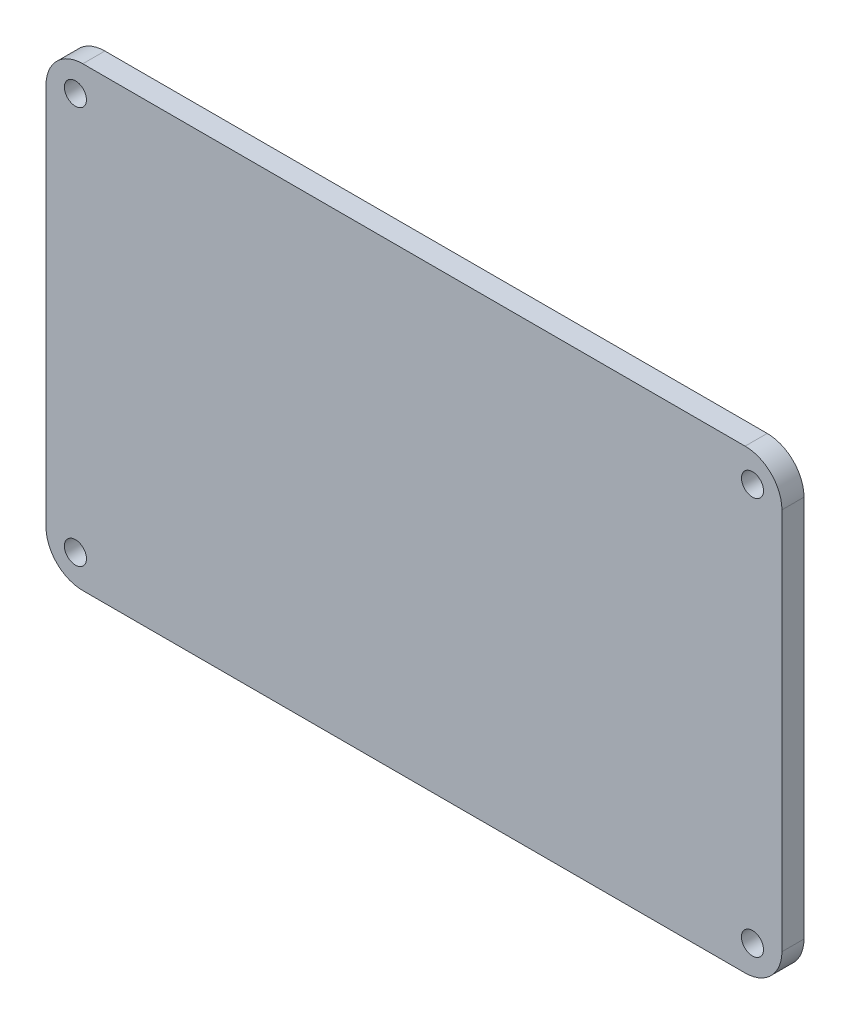
SolidWorks part; units mm, degrees
ref_plane "前视基准面" through (0, 0, 0) normal (0, 0, 1) x (1, 0, 0)
ref_plane "上视基准面" through (0, 0, 0) normal (0, 1, 0) x (1, 0, 0)
ref_plane "右视基准面" through (0, 0, 0) normal (1, 0, 0) x (0, 0, -1)
other "Configuration Table"
sketch "草图1" plane through (0, 0, 0) normal (0, 0, 1) x (1, 0, 0)
  line L1 (-45, 31) -> (45, 31)
  line L2 (-50, 26) -> (-50, -26)
  line L3 (-45, -31) -> (45, -31)
  line L4 (50, 26) -> (50, -26)
  line L5 (-50, 31) -> (50, -31) construction
  line L6 (-50, -31) -> (50, 31) construction
  arc A0 (-50, 26) -> (-45, 31) centre (-45, 26) cw
  arc A1 (50, 26) -> (45, 31) centre (45, 26) ccw
  arc A2 (45, -31) -> (50, -26) centre (45, -26) ccw
  arc A3 (-45, -31) -> (-50, -26) centre (-45, -26) cw
  point P0 (0, 0)
  dimension "D3" = 5
  dimension "D4" = 5
  dimension "D5" = 5
  dimension "D6" = 5
  dimension "D1" = 100
  dimension "D2" = 62
extrude "凸台-拉伸1" add sketch "草图1" along normal blind 3
sketch "草图2" plane through (0, 0, 3) normal (0, 0, 1) x (1, 0, 0)
  line L0 (45, 31) -> (-45, 31) construction
  line L1 (-50, 26) -> (-50, -26) construction
  circle A0 centre (-46, 27) radius 1.5
  circle A1 centre (46, 27) radius 1.5
  circle A2 centre (-46, -27) radius 1.5
  circle A3 centre (46, -27) radius 1.5
  dimension "D1" = 3
  dimension "D2" = 4
  dimension "D3" = 4
  dimension "D4" = 2
  dimension "D5" = 2
extrude "切除-拉伸1" cut sketch "草图2" against normal blind 3
